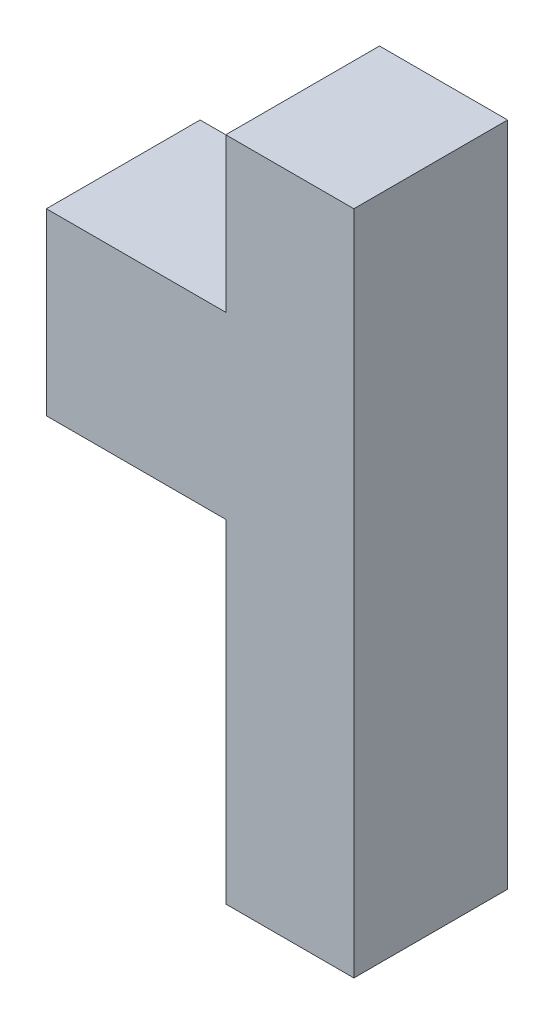
SolidWorks part; units mm, degrees
ref_plane "Front Plane" through (0, 0, 0) normal (0, 0, 1) x (1, 0, 0)
ref_plane "Top Plane" through (0, 0, 0) normal (0, 1, 0) x (1, 0, 0)
ref_plane "Right Plane" through (0, 0, 0) normal (1, 0, 0) x (0, 0, -1)
sketch "Sketch1" plane through (0, 0, 0) normal (0, 0, 1) x (1, 0, 0)
  line L0 (-12.5, 70) -> (-47.5, 70) construction
  line L1 (-12.5, 70) -> (12.5, 70)
  line L2 (-12.5, 70) -> (-12.5, 40)
  line L3 (-12.5, -70) -> (12.5, -70)
  line L4 (12.5, 70) -> (12.5, -70)
  line L5 (-12.5, 70) -> (12.5, -70) construction
  line L6 (-12.5, -70) -> (12.5, 70) construction
  line L7 (-47.5, 70) -> (-47.5, 40) construction
  line L8 (-12.5, 5) -> (-12.5, -70)
  line L9 (-47.5, 40) -> (-12.5, 40)
  line L10 (-47.5, 40) -> (-47.5, 5)
  line L11 (-47.5, 5) -> (-12.5, 5)
  point P0 (0, 0)
extrude "Boss-Extrude1" add sketch "Sketch1" along normal blind 30
sketch "Sketch2" plane through (0, 0, 0) normal (0, 1, 0) x (1, 0, 0)
  line L0 (-12.5, -30) -> (12.5, 0) construction
  line L1 (-12.5, -30) -> (12.5, -30)
  line L2 (-12.5, -30) -> (-12.5, 0)
  line L3 (-12.5, 0) -> (12.5, 0)
  line L4 (12.5, -30) -> (12.5, 0)
  line L5 (-12.5, 0) -> (12.5, -30) construction
  line L7 (-2.5, -10) -> (2.5, -10)
  line L8 (-2.5, -10) -> (-2.5, -20)
  line L9 (-2.5, -20) -> (2.5, -20)
  line L10 (2.5, -10) -> (2.5, -20)
  line L11 (-2.5, -10) -> (2.5, -20) construction
  line L12 (-2.5, -20) -> (2.5, -10) construction
  point P6 (0, -15)
extrude "Cut-Extrude1" cut sketch "Sketch2" along normal blind 10 from surface at -70 starting at face at (0, -70, 15)
sketch "Sketch3" plane through (0, 0, 0) normal (1, 0, 0) x (0, 0, -1)
  line L0 (-20, -60) -> (-10, -70) construction
  line L1 (-20, -70) -> (-10, -60) construction
  line L2 (-20, -70) -> (-10, -70) construction
  line L3 (-20, -60) -> (-20, -70) construction
  circle A1 centre (-15, -65) radius 2.5
extrude "Cut-Extrude2" cut sketch "Sketch3" against normal blind 10 and the other way blind 10
fillet "Fillet1" radius 1 2 edges at (0, -70, 10) (0, -70, 20)
